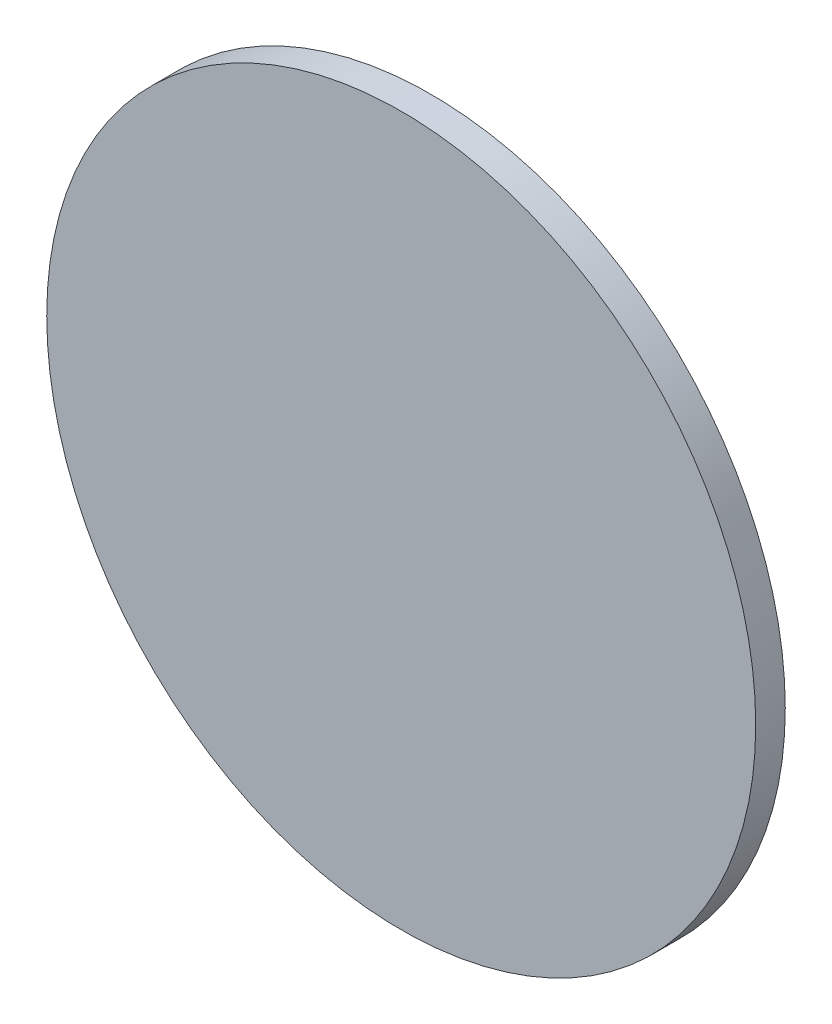
SolidWorks part; units mm, degrees
ref_plane "Front Plane" through (0, 0, 0) normal (0, 0, 1) x (1, 0, 0)
ref_plane "Top Plane" through (0, 0, 0) normal (0, 1, 0) x (1, 0, 0)
ref_plane "Right Plane" through (0, 0, 0) normal (1, 0, 0) x (0, 0, -1)
sketch "Sketch1" plane through (0, 0, 0) normal (0, 0, 1) x (1, 0, 0)
  circle A0 centre (0, 0) radius 58.6265 construction
  circle A1 centre (0, 0) radius 60
  dimension "D1" = 120
extrude "Boss-Extrude1" add sketch "Sketch1" along normal blind 5
